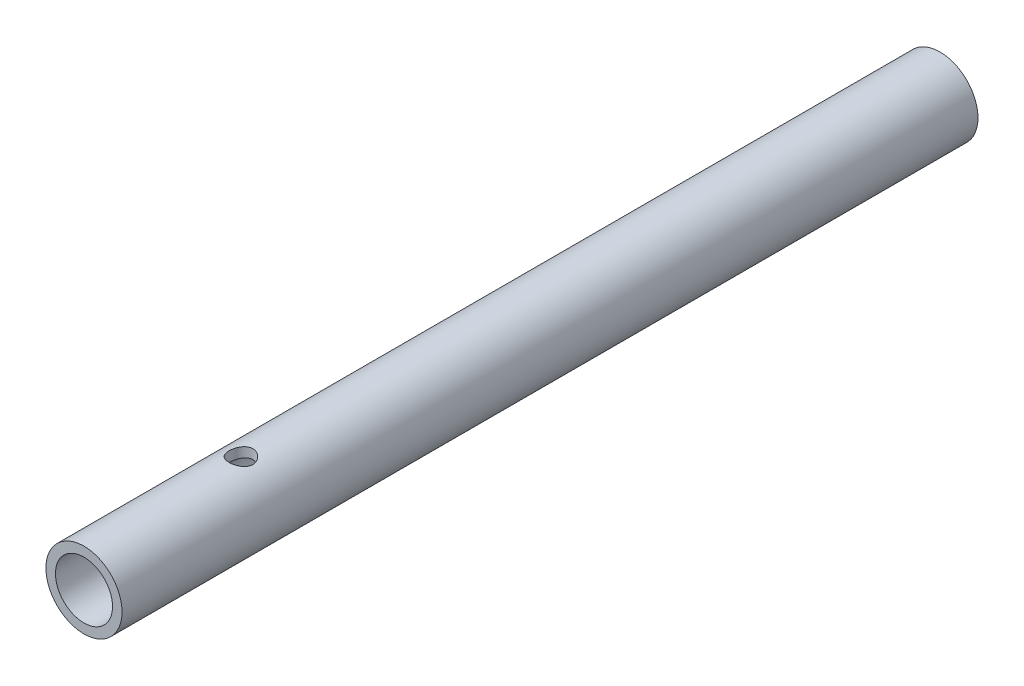
SolidWorks part; units mm, degrees
ref_plane "Plan de face" through (0, 0, 0) normal (0, 0, 1) x (1, 0, 0)
ref_plane "Plan de dessus" through (0, 0, 0) normal (0, 1, 0) x (1, 0, 0)
ref_plane "Plan de droite" through (0, 0, 0) normal (1, 0, 0) x (0, 0, -1)
sketch "Esquisse1" plane through (0, 0, 0) normal (0, 0, 1) x (1, 0, 0)
  circle A0 centre (0, 0) radius 4
  dimension "D1" = 8
extrude "Boss.-Extru.1" add sketch "Esquisse1" against normal blind 90
sketch "Esquisse2" plane through (0, 0, 0) normal (0, 1, 0) x (1, 0, 0)
  line L0 (-4, 0) -> (4, 0) construction
  circle A0 centre (0, 16.5) radius 1.25
  dimension "D1" = 16.5
  dimension "D2" = 2.5
extrude "Enlèv. mat.-Extru.1" cut sketch "Esquisse2" against normal mid plane 20
hole_wizard "Trou taraudé M3x0.51" positions "Esquisse4" profile "Esquisse5" tap size "M3x0.5" standard "Ansi Metric"
sketch "Esquisse4" plane through (0, 0, -90) normal (0, 0, -1) x (-1, 0, 0)
  point P0 (0, 0)
sketch "Esquisse5" plane through (0, 0, -90) normal (1, 0, 0) x (0, 1, 0)
  line L0 (0, 0) -> (0, 13.2511)
  line L1 (0, 13.2511) -> (1.25, 12.5)
  line L2 (1.25, 12.5) -> (1.25, 0)
  line L5 (1.25, 0) -> (0, 0)
  line L10 (0, 13.2511) -> (-1.25, 12.5) construction
  line L11 (0, -6.35) -> (0, 107.95) construction
  dimension "Diamètre du trou pour taraudage" = 2.5
  dimension "Profondeur du trou pour taraudage" = 12.5
  dimension "Angle de pointe" = 118
cosmetic thread "Filetage de perçage1" parameters "D1"=10, "D2"=3
sketch "Esquisse6" plane through (0, 0, 0) normal (0, 0, 1) x (1, 0, 0)
  circle A0 centre (0, 0) radius 3
  circle A1 centre (0, 0) radius 4 construction
  dimension "D1" = 1
  dimension "D2" = 6
extrude "Enlèv. mat.-Extru.2" cut sketch "Esquisse6" against normal through all
